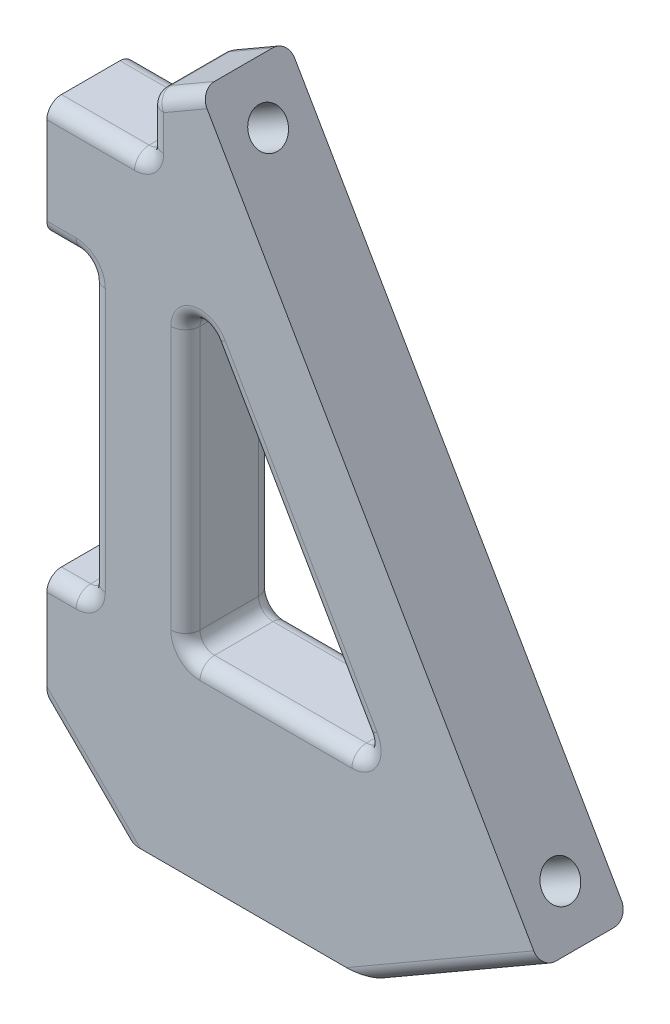
SolidWorks part; units mm, degrees
ref_plane "Спереди" through (0, 0, 0) normal (0, 0, 1) x (1, 0, 0)
ref_plane "Сверху" through (0, 0, 0) normal (0, 1, 0) x (1, 0, 0)
ref_plane "Справа" through (0, 0, 0) normal (1, 0, 0) x (0, 0, -1)
sketch "Эскиз1" plane through (0, 0, 0) normal (0, 0, 1) x (1, 0, 0)
  line L0 (0, 5) -> (5, 0)
  line L1 (5, 0) -> (22.5, 0)
  line L2 (22.5, 0) -> (33.8247, 6.5383)
  line L3 (33.8247, 6.5383) -> (10.4641, 47)
  line L4 (10.4641, 47) -> (7, 45)
  line L5 (7, 45) -> (7, 41)
  line L6 (7, 41) -> (0, 41)
  line L7 (0, 41) -> (0, 33)
  line L8 (0, 33) -> (3, 33)
  line L9 (3, 33) -> (3, 13)
  line L10 (3, 13) -> (0, 13)
  line L11 (0, 13) -> (0, 5)
  dimension "D1" = 5
  dimension "D2" = 45
  dimension "D3" = 41
  dimension "D4" = 8
  dimension "D5" = 8
  dimension "D6" = 3
  dimension "D7" = 30
  dimension "D8" = 4
  dimension "D9" = 7
  dimension "D10" = 4
  dimension "D11" = 22.5
extrude "Бобышка-Вытянуть1" add sketch "Эскиз1" along normal blind 6
sketch "Эскиз2" plane through (0, 0, 6) normal (0, 0, 1) x (1, 0, 0)
  line L0 (9.4833, 32) -> (9.4833, 13)
  line L1 (9.4833, 13) -> (20.8756, 13)
  line L2 (21.7417, 14.5) -> (11.3494, 32.5)
  line L4 (3, 13) -> (0, 13) construction
  line L5 (3, 33) -> (3, 13) construction
  line L6 (33.8247, 6.5383) -> (10.4641, 47) construction
  line L7 (3, 19.3036) -> (9.4833, 19.3036) construction
  line L8 (0, 33) -> (3, 33) construction
  line L9 (11.5989, 32.0679) -> (17.2136, 35.3095) construction
  arc A0 (11.3494, 32.5) -> (9.4833, 32) centre (10.4833, 32) ccw
  arc A1 (20.8756, 13) -> (21.7417, 14.5) centre (20.8756, 14) ccw
  dimension "D1" = 1
extrude "Вырез-Вытянуть1" cut sketch "Эскиз2" against normal blind 6
sketch "Эскиз3" plane through (0, 0, 0) normal (-1, 0, 0) x (0, 0, 1)
  line L4 (6, 5) -> (0, 5) construction
  line L5 (6, 13) -> (6, 5) construction
  line L6 (6, 33) -> (0, 33) construction
  line L7 (6, 41) -> (6, 33) construction
  circle A0 centre (3, 37) radius 1.25
  circle A1 centre (3, 9) radius 1.25
  point P4 (6, 9)
  point P5 (3, 5)
  point P8 (6, 37)
  point P11 (3, 33)
  dimension "D1" = 2.5
extrude "Вырез-Вытянуть2" cut sketch "Эскиз3" against normal blind 8
sketch "Эскиз4" plane through (0, 0, 0) normal (0, -1, 0) x (1, 0, 0)
  line L2 (5, 0) -> (22.5, 0) construction
  line L3 (5, 6) -> (5, 0) construction
  circle A0 centre (13.75, 3) radius 1.25
  point P0 (5, 3)
  point P1 (13.75, 0)
  dimension "D1" = 2.5
extrude "Вырез-Вытянуть3" cut sketch "Эскиз4" against normal blind 8
sketch "Эскиз5" plane through (28.1997, 16.2811, 0) normal (0.866, 0.5, 0) x (0, 0, -1)
  line L2 (-3, 32.1106) -> (-3, 35.4711) construction
  line L3 (-3, -7.8894) -> (-3, -11.25) construction
  line L5 (-6, 35.4711) -> (0, 35.4711) construction
  line L6 (-6, -11.25) -> (0, -11.25) construction
  circle A0 centre (-3, 32.1106) radius 1.25
  circle A1 centre (-3, -7.8894) radius 1.25
  dimension "D2" = 2.5
  dimension "D1" = 40
extrude "Вырез-Вытянуть4" cut sketch "Эскиз5" against normal blind 4
fillet "Скругление2" radius 1 31 edges at (10.2245, 32.9659, 6) (16.5455, 23.5, 6) (21.7417, 13.5, 6) (15.1795, 13, 6) (2.5, 2.5, 6) (2.5, 2.5, 0) (21.7417, 13.5, 0) (15.1795, 13, 0) (9.4833, 22.5, 0) (10.2245, 32.9659, 0) (9.4833, 22.5, 6) (16.5455, 23.5, 0) (7, 43, 0) (7, 43, 6) (1.5, 33, 0) (1.5, 13, 0) (1.5, 33, 6) (1.5, 13, 6) (8.7321, 46, 0) (8.7321, 46, 6) (3.5, 41, 0) (3.5, 41, 6) (7, 45, 3) (7, 41, 3) (28.1623, 3.2692, 0) (28.1623, 3.2692, 6) (3, 23, 0) (3, 23, 6) (3, 33, 3) (3, 13, 3) (9.4833, 13, 3)
